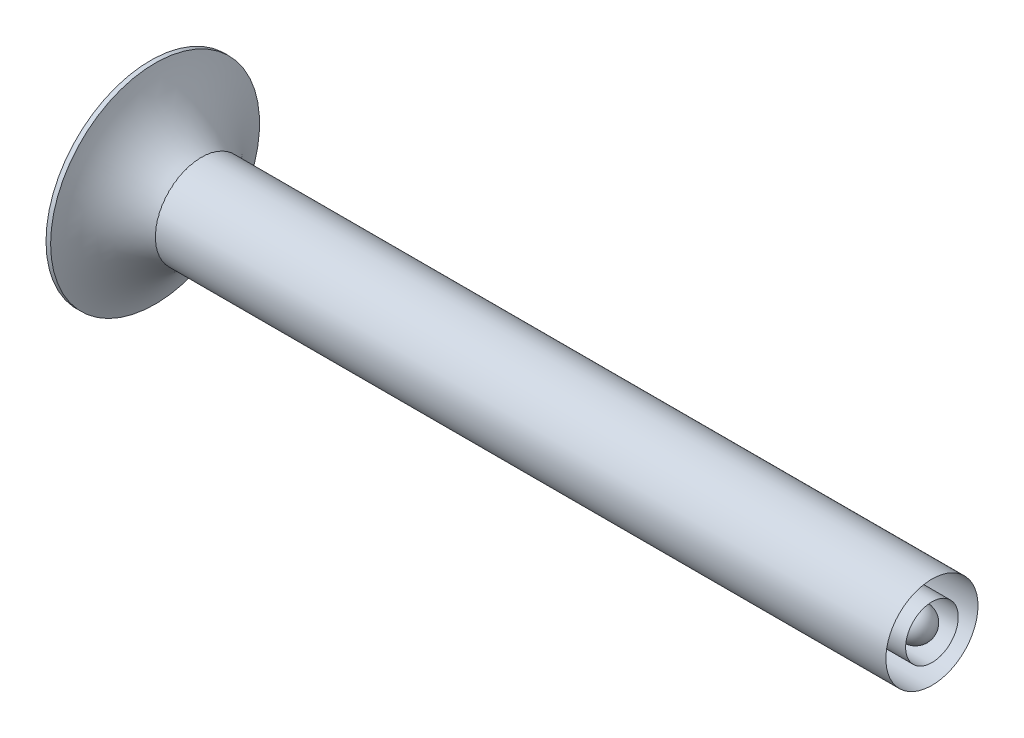
SolidWorks part; units mm, degrees
ref_plane "Front Plane" through (0, 0, 0) normal (0, 0, 1) x (1, 0, 0)
ref_plane "Top Plane" through (0, 0, 0) normal (0, 1, 0) x (1, 0, 0)
ref_plane "Right Plane" through (0, 0, 0) normal (1, 0, 0) x (0, 0, -1)
sketch "Sketch1" plane through (0, 0, 0) normal (0, 0, 1) x (1, 0, 0)
  line L0 (0, -4.0323) -> (0, 0)
  line L1 (0, 4.0322) -> (0.1778, 4.0322) construction
  line L2 (0.1778, 4.0322) -> (1.67, 2.54) construction
  line L3 (1.67, 2.54) -> (3.8608, 1.27) construction
  line L4 (3.8608, 1.27) -> (3.8608, -1.27) construction
  line L5 (3.8608, -1.27) -> (1.67, -2.54) construction
  line L6 (1.67, -2.54) -> (0.1778, -4.0323) construction
  line L7 (0.1778, -4.0323) -> (0, -4.0323)
  line L8 (0.1778, 4.0322) -> (0.1778, -4.0323) construction
  line L9 (1.67, 2.54) -> (1.67, -2.54) construction
  line L10 (0, 0) -> (29.5275, 0) construction
  line L11 (3.8608, 1.27) -> (24.7458, 1.27) construction
  line L12 (3.8608, -1.27) -> (5.2705, -1.27)
  line L13 (26.6751, -1.016) -> (29.6104, -0.6296)
  line L14 (29.6104, 0.6296) -> (24.7458, 1.27) construction
  line L15 (24.7458, 1.27) -> (24.7458, -1.27) construction
  line L16 (29.6104, -0.6296) -> (34.3924, 0) construction
  line L17 (34.3924, 0) -> (29.6104, 0.6296) construction
  line L18 (0, 0) -> (30.1625, 0)
  line L19 (0, 0) -> (0, 4.0322) construction
  line L20 (5.2705, -1.27) -> (7.1998, -1.016)
  line L22 (7.1998, -1.016) -> (26.6751, -1.016)
  line L23 (5.2705, -1.27) -> (24.7458, -1.27) construction
  line L24 (24.7458, -1.27) -> (26.6751, -1.016) construction
  line L25 (7.1998, -1.016) -> (7.1998, 1.016) construction
  arc A0 (30.1625, 0) -> (29.6104, -0.6296) centre (29.5275, 0) cw
  arc A1 (29.6104, 0.6296) -> (30.1625, 0) centre (29.5275, 0) cw construction
  arc A2 (3.8608, -1.27) -> (0.1778, -4.0323) centre (3.8608, -5.1065) ccw
  point P3 (7.1998, 0)
  point P14 (3.8608, 0)
  point P26 (3.8608, -4.2849)
  dimension "D10" = 0.635
  dimension "D1" = 8.0645
  dimension "D2" = 3.683
  dimension "D3" = 45
  dimension "D4" = 45
  dimension "D5" = 5.08
  dimension "D6" = 2.54
  dimension "D7" = 3.8608
  dimension "D8" = 30.1625
  dimension "D9" = 15
  dimension "D11" = 7.5
  dimension "D12" = 2.032
  dimension "D13" = 24.892
revolve "Revolve1" add sketch "Sketch1" angle 360 about L18
sketch "Sketch2" plane through (0, 0, 0) normal (1, 0, 0) x (0, 0, -1)
  circle A1 centre (0, 0) radius 1.016
  circle A2 centre (0, 0) radius 1.016 construction
surface "Max Pre-Drill Diameter" sketch "Sketch2"
sketch "Sketch3" plane through (0, 0, 0) normal (-1, 0, 0) x (0, 0, 1)
  circle A0 centre (0, 0) radius 1.778
  dimension "D1" = 3.556
surface "Thread Diameter" sketch "Sketch3"
